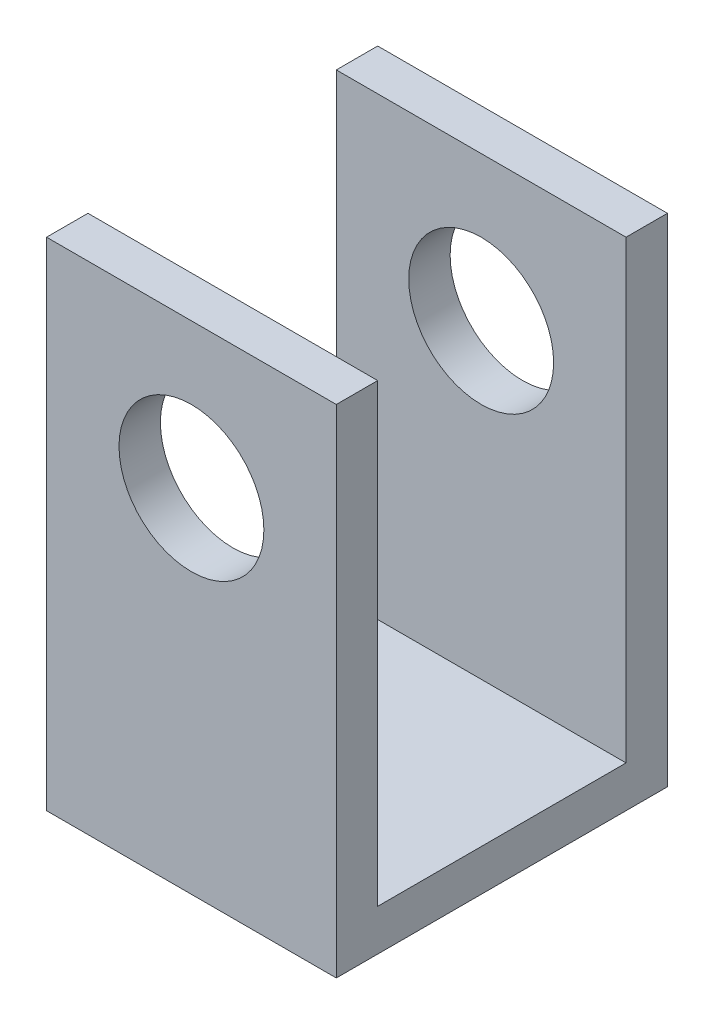
SolidWorks part; units mm, degrees
ref_plane "Front Plane" through (0, 0, 0) normal (0, 0, 1) x (1, 0, 0)
ref_plane "Top Plane" through (0, 0, 0) normal (0, 1, 0) x (1, 0, 0)
ref_plane "Right Plane" through (0, 0, 0) normal (1, 0, 0) x (0, 0, -1)
sketch "Sketch1" plane through (0, 0, 0) normal (0, 0, 1) x (1, 0, 0)
  line L0 (35, 120) -> (35, 0) construction
  line L1 (0, 0) -> (70, 0)
  line L2 (0, 0) -> (0, 120)
  line L3 (0, 120) -> (70, 120)
  line L4 (70, 0) -> (70, 120)
  line L5 (70, 120) -> (70, 102.4554) construction
  circle A2 centre (35, 85) radius 17.5
  dimension "D1" = 70
  dimension "D4" = 35
  dimension "D2" = 120
  dimension "D3" = 35
extrude "Boss-Extrude3" add sketch "Sketch1" along normal blind 80
ref_plane "Plane1" through (0, 120, 0) normal (0, 1, 0) x (1, 0, 0)
sketch "Sketch2" plane through (0, 120, 0) normal (0, 1, 0) x (1, 0, 0)
  line L0 (0, -80) -> (0, 0) construction
  line L1 (0, -10) -> (70, -10)
  line L2 (0, -10) -> (0, -70)
  line L3 (0, -70) -> (70, -70)
  line L4 (70, -10) -> (70, -70)
  line L5 (70, -80) -> (70, 0) construction
  line L6 (70, 0) -> (0, 0) construction
  line L7 (70, -80) -> (0, -80) construction
  dimension "D1" = 10
  dimension "D2" = 10
extrude "Cut-Extrude1" cut sketch "Sketch2" against normal blind 110
